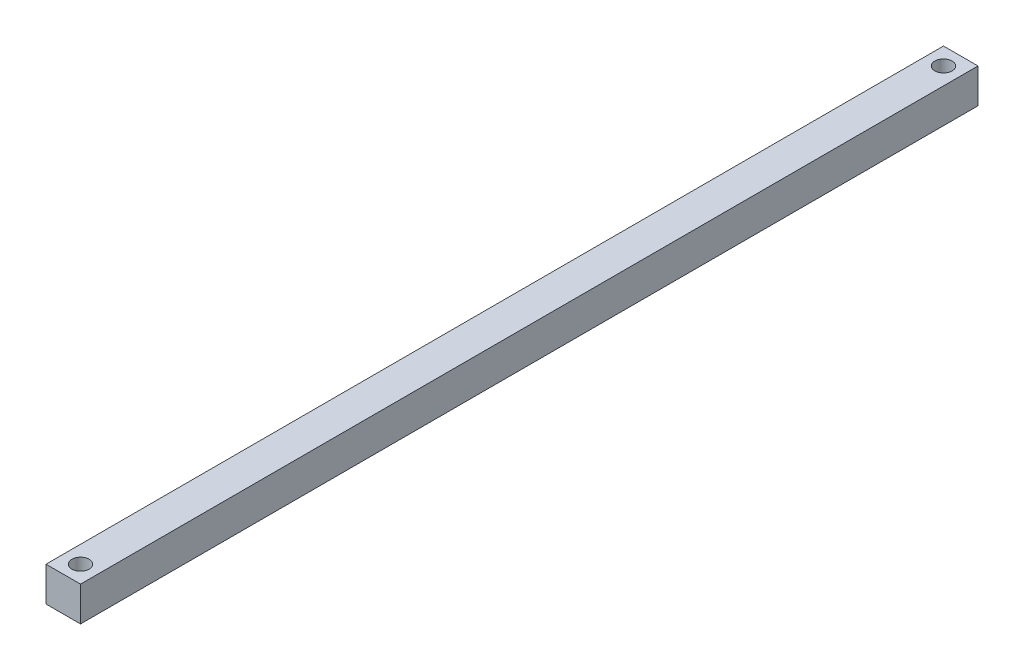
SolidWorks part; units mm, degrees
ref_plane "Plan de face" through (0, 0, 0) normal (0, 0, 1) x (1, 0, 0)
ref_plane "Plan de dessus" through (0, 0, 0) normal (0, 1, 0) x (1, 0, 0)
ref_plane "Plan de droite" through (0, 0, 0) normal (1, 0, 0) x (0, 0, -1)
sketch "Esquisse2" plane through (0, 0, 0) normal (0, 1, 0) x (1, 0, 0)
  line L1 (0, 0) -> (-10, 0)
  line L2 (0, 0) -> (0, 260)
  line L3 (0, 260) -> (-10, 260)
  line L4 (-10, 0) -> (-10, 260)
  dimension "D1" = 10
  dimension "D2" = 260
extrude "Boss.-Extru.1" add sketch "Esquisse2" along normal blind 10
sketch "Esquisse3" plane through (0, 10, 0) normal (0, 1, 0) x (1, 0, 0)
  line L0 (-5, 0) -> (-5, 260) construction
  line L1 (-10, 0) -> (0, 0) construction
  line L2 (0, 260) -> (-10, 260) construction
  circle A0 centre (-5, 255) radius 2.5
  circle A1 centre (-5, 5) radius 2.5
  dimension "D1" = 5
  dimension "D2" = 5
  dimension "D3" = 5
  dimension "D4" = 5
extrude "Enlèv. mat.-Extru.1" cut sketch "Esquisse3" against normal blind 10
